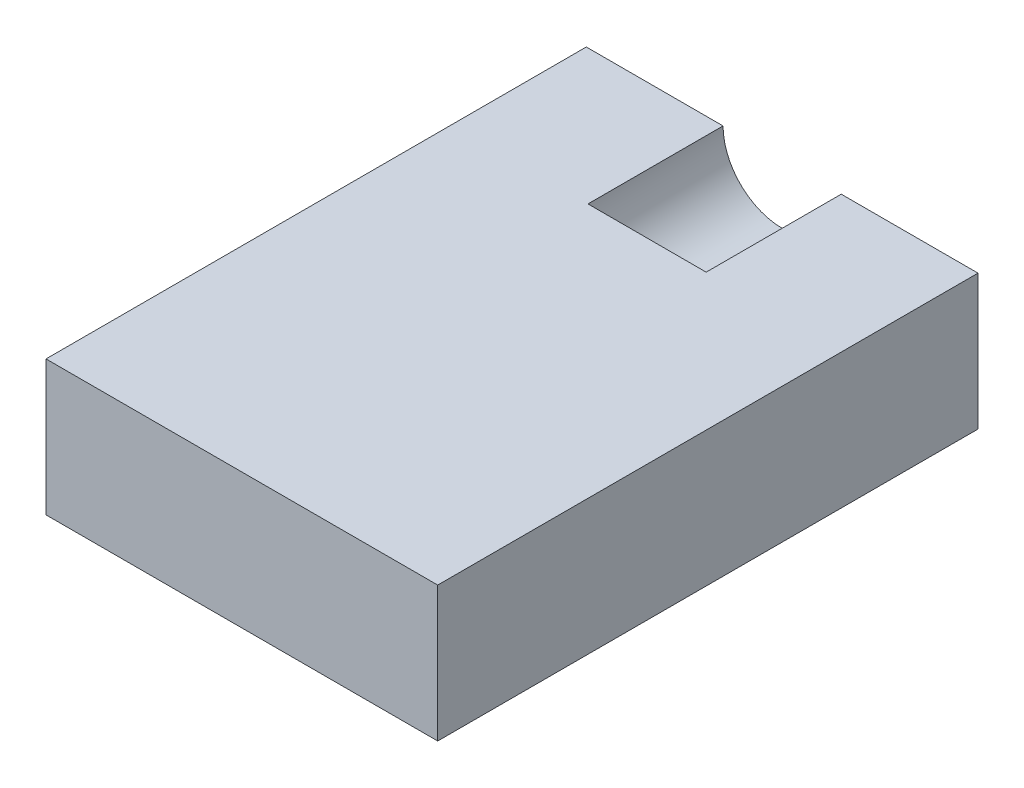
SolidWorks part; units mm, degrees
ref_plane "Front Plane" through (0, 0, 0) normal (0, 0, 1) x (1, 0, 0)
ref_plane "Top Plane" through (0, 0, 0) normal (0, 1, 0) x (1, 0, 0)
ref_plane "Right Plane" through (0, 0, 0) normal (1, 0, 0) x (0, 0, -1)
sketch "Sketch1" plane through (0, 0, 0) normal (0, 0, 1) x (1, 0, 0)
  line L1 (-18.415, 6.35) -> (18.415, 6.35)
  line L2 (-18.415, 6.35) -> (-18.415, -6.35)
  line L3 (-18.415, -6.35) -> (18.415, -6.35)
  line L4 (18.415, 6.35) -> (18.415, -6.35)
  line L5 (-18.415, 6.35) -> (18.415, -6.35) construction
  line L6 (-18.415, -6.35) -> (18.415, 6.35) construction
  point P0 (0, 0)
  dimension "D1" = 12.7
  dimension "D2" = 36.83
extrude "Boss-Extrude1" add sketch "Sketch1" along normal blind 50.8
sketch "Sketch3" plane through (0, 0, 0) normal (0, 0, 1) x (1, 0, 0)
  line L0 (18.415, 6.35) -> (-18.415, 6.35) construction
  circle A0 centre (0, 6.35) radius 5.5562
extrude "Cut-Extrude1" cut sketch "Sketch3" along normal blind 12.7
